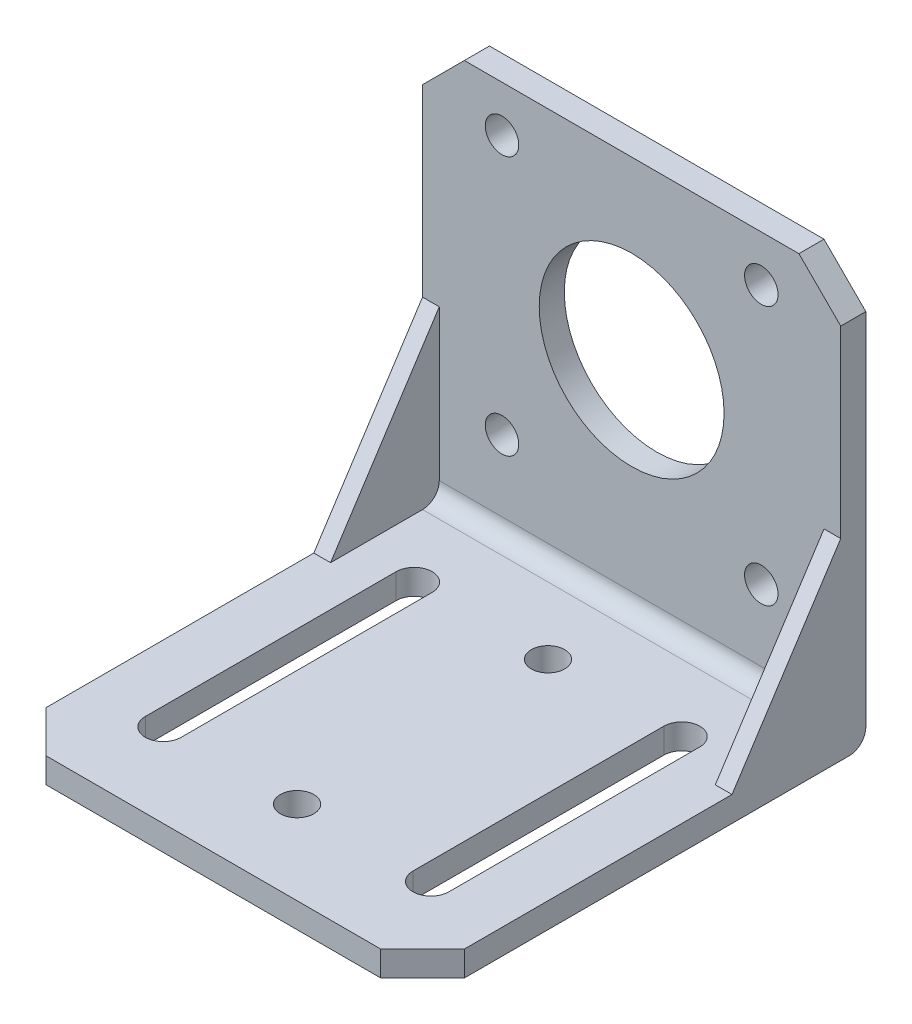
SolidWorks part; units mm, degrees
ref_plane "Alzado" through (0, 0, 0) normal (0, 0, 1) x (1, 0, 0)
ref_plane "Planta" through (0, 0, 0) normal (0, 1, 0) x (1, 0, 0)
ref_plane "Vista lateral" through (0, 0, 0) normal (1, 0, 0) x (0, 0, -1)
sketch "Croquis2" plane through (0, 0, 0) normal (1, 0, 0) x (0, 0, -1)
  line L0 (0, 0) -> (-53, 0)
  line L1 (-53, 0) -> (-53, 3)
  line L2 (-53, 3) -> (-3, 3)
  line L3 (-3, 3) -> (-3, 50)
  line L4 (-3, 50) -> (0, 50)
  line L5 (0, 50) -> (0, 0)
  dimension "D1" = 53
  dimension "D2" = 3
  dimension "D3" = 3
  dimension "D4" = 50
extrude "Saliente-Extruir1" add sketch "Croquis2" along normal mid plane 50
sketch "Croquis3" plane through (25, 0, 0) normal (1, 0, 0) x (0, 0, -1)
  line L0 (-16, 3) -> (-3, 23)
  line L1 (-3, 3) -> (-53, 3) construction
  line L2 (-3, 50) -> (-3, 3) construction
  dimension "D1" = 20
  dimension "D2" = 13
rib "Nervio1" sketch "Croquis3" sketch "Croquis3" thickness 2 extrusion direction parallel to sketch draft on no parameters "D1"=2
mirror "Simetría1" about plane through (0, 0, 0) normal (1, 0, 0) of "Nervio1"
fillet "Redondeo1" radius 2 2 edges at (0, 3, 3) (0, 0, 0)
sketch "Croquis4" plane through (0, 0, 3) normal (0, 0, 1) x (1, 0, 0)
  line L0 (25, 0) -> (-25, 0) construction
  line L1 (0, 29) -> (0, 47.7119) construction
  line L2 (0, 29) -> (15.2527, 29) construction
  circle A0 centre (0, 29) radius 11.05
  circle A1 centre (-15.5, 44.5) radius 2
  circle A2 centre (15.5, 44.5) radius 2
  circle A3 centre (-15.5, 13.5) radius 2
  circle A4 centre (15.5, 13.5) radius 2
  dimension "D1" = 22.1
  dimension "D5" = 4
  dimension "D2" = 29
  dimension "D3" = 15.5
  dimension "D4" = 15.5
extrude "Cortar-Extruir1" cut sketch "Croquis4" against normal through all
chamfer "Chaflán1" distance 5 angle 45 4 edges at (25, 1.5, 53) (-25, 1.5, 53) (-25, 50, 1.5) (25, 50, 1.5)
sketch "Croquis5" plane through (0, 3, 0) normal (0, 1, 0) x (1, 0, 0)
  line L0 (-16, -13) -> (-16, -43) construction
  line L1 (-13.85, -13) -> (-13.85, -43)
  line L2 (-18.15, -13) -> (-18.15, -43)
  line L3 (0, -5) -> (0, -53) construction
  line L4 (23, -5) -> (-23, -5) construction
  line L5 (20, -53) -> (-20, -53) construction
  line L7 (16, -13) -> (16, -43) construction
  line L8 (13.85, -13) -> (13.85, -43)
  line L9 (18.15, -13) -> (18.15, -43)
  arc A0 (-13.85, -13) -> (-18.15, -13) centre (-16, -13) ccw
  arc A1 (-18.15, -43) -> (-13.85, -43) centre (-16, -43) ccw
  arc A2 (13.85, -13) -> (18.15, -13) centre (16, -13) cw
  arc A3 (18.15, -43) -> (13.85, -43) centre (16, -43) cw
  point P2 (-16, -28)
  point P15 (16, -28)
  dimension "D2" = 2.15
  dimension "D1" = 25
  dimension "D3" = 16
  dimension "D4" = 30
extrude "Cortar-Extruir2" cut sketch "Croquis5" against normal through all
sketch "Croquis6" plane through (0, 3, 0) normal (0, 1, 0) x (1, 0, 0)
  line L0 (-18.15, -28) -> (18.15, -28) construction
  line L1 (-18.15, -13) -> (-18.15, -43) construction
  line L2 (18.15, -43) -> (18.15, -13) construction
  line L3 (0, -28) -> (0, 0) construction
  circle A0 centre (0, -13) radius 2
  circle A1 centre (0, -43) radius 2
  dimension "D1" = 4
  dimension "D2" = 15
extrude "Cortar-Extruir3" cut sketch "Croquis6" against normal through all
